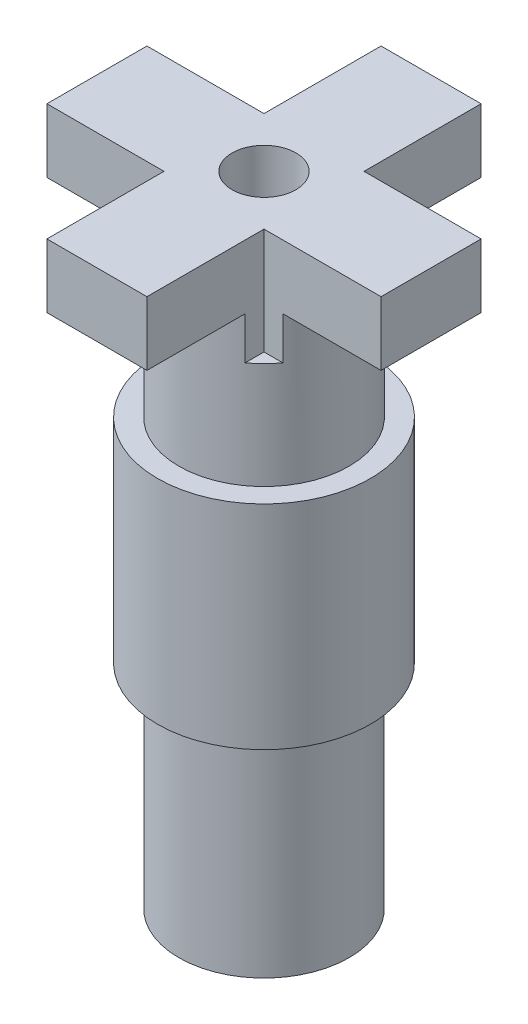
SolidWorks part; units mm, degrees
ref_plane "前视基准面" through (0, 0, 0) normal (0, 0, 1) x (1, 0, 0)
ref_plane "上视基准面" through (0, 0, 0) normal (0, 1, 0) x (1, 0, 0)
ref_plane "右视基准面" through (0, 0, 0) normal (1, 0, 0) x (0, 0, -1)
other "Configuration Table"
sketch "草图1" plane through (0, 0, 0) normal (0, 1, 0) x (1, 0, 0)
  circle A0 centre (0, 0) radius 5
  dimension "D1" = 10
extrude "凸台-拉伸4" add sketch "草图1" along normal blind 10
sketch "草图4" plane through (0, 10, 0) normal (0, 1, 0) x (1, 0, 0)
  circle A0 centre (0, 0) radius 4
  dimension "D1" = 8
extrude "凸台-拉伸5" add sketch "草图4" along normal blind 10
sketch "草图5" plane through (0, 0, 0) normal (0, -1, 0) x (1, 0, 0)
  circle A0 centre (0, 0) radius 4
  dimension "D1" = 8
extrude "凸台-拉伸6" add sketch "草图5" along normal blind 10
sketch "草图6" plane through (0, 20, 0) normal (0, 1, 0) x (1, 0, 0)
  line L1 (-7.85, -2.35) -> (7.85, -2.35)
  line L2 (-7.85, -2.35) -> (-7.85, 2.35)
  line L3 (-7.85, 2.35) -> (7.85, 2.35)
  line L4 (7.85, -2.35) -> (7.85, 2.35)
  line L5 (-7.85, -2.35) -> (7.85, 2.35) construction
  line L6 (-7.85, 2.35) -> (7.85, -2.35) construction
  line L7 (-2.35, 7.85) -> (2.35, 7.85)
  line L8 (-2.35, 7.85) -> (-2.35, -7.85)
  line L9 (-2.35, -7.85) -> (2.35, -7.85)
  line L10 (2.35, 7.85) -> (2.35, -7.85)
  line L11 (-2.35, 7.85) -> (2.35, -7.85) construction
  line L12 (-2.35, -7.85) -> (2.35, 7.85) construction
  point P0 (0, 0)
  point P6 (0, 0)
  circle M5 centre (0, 0) radius 4
  dimension "D1" = 15.7
  dimension "D2" = 4.7
  dimension "D3" = 15.7
  dimension "D4" = 4.7
extrude "凸台-拉伸7" add sketch "草图6" against normal blind 3 contours L3 L2 L1 M5 | L10 L7 L8 M5 | L1 L4 L3 M5 | L10 L8 L9 M5 | L10 L1 L8 M5 | L3 L10 L1 M5 | L10 L8 L3 M5 | L8 L3 L1 M5 | L10 L3 L8 L1
sketch "草图7" plane through (0, 20, 0) normal (0, 1, 0) x (1, 0, 0)
  line L0 (-3.2369, 2.35) -> (3.2369, 2.35)
  line L1 (3.2369, 2.35) -> (3.2369, -2.35)
  line L2 (3.2369, -2.35) -> (-3.2369, -2.35)
  line L3 (-3.2369, -2.35) -> (-3.2369, 2.35)
  line L4 (-2.35, 3.2369) -> (-2.35, -3.2369)
  line L5 (-2.35, -3.2369) -> (2.35, -3.2369)
  line L6 (2.35, -3.2369) -> (2.35, -7.85) construction
  line L7 (2.35, -3.2369) -> (2.35, 3.2369)
  line L8 (2.35, 3.2369) -> (-2.2295, 3.2369)
  circle A0 centre (0, 0) radius 4
  arc M1 (-3.2369, -2.35) -> (-2.35, -3.2369) centre (0, 0) ccw
  arc M5 (2.35, -3.2369) -> (3.2369, -2.35) centre (0, 0) ccw
  arc M9 (3.2369, 2.35) -> (2.35, 3.2369) centre (0, 0) ccw
  arc M13 (-2.35, 3.2369) -> (-3.2369, 2.35) centre (0, 0) ccw
extrude "切除-拉伸1" cut sketch "草图7" against normal blind 5 contours L4 L2 M1 | L7 L2 M5 | L7 L0 M9 | L4 L0 M13
sketch "草图8" plane through (0, 20, 0) normal (0, 1, 0) x (1, 0, 0)
  circle A0 centre (0, 0) radius 1.5
  dimension "D1" = 3
extrude "切除-拉伸2" cut sketch "草图8" against normal through all
